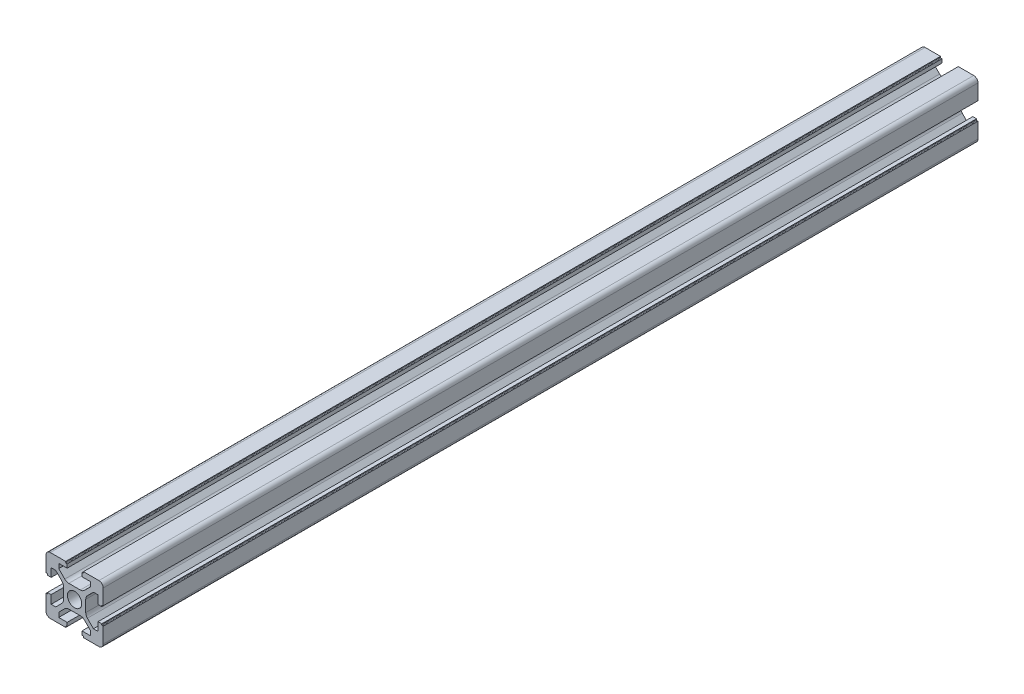
SolidWorks part; units mm, degrees
ref_plane "Спереди" through (0, 0, 0) normal (0, 0, 1) x (1, 0, 0)
ref_plane "Сверху" through (0, 0, 0) normal (0, 1, 0) x (1, 0, 0)
ref_plane "Справа" through (0, 0, 0) normal (1, 0, 0) x (0, 0, -1)
sketch "Sketch1" plane through (0, 0, 0) normal (0, 0, 1) x (1, 0, 0)
  line L0 (0, 10) -> (0, -10) construction
  line L1 (-10, -10) -> (10, -10) construction
  line L2 (-10, -10) -> (-10, 10) construction
  line L3 (-10, 10) -> (10, 10) construction
  line L4 (10, -10) -> (10, 10) construction
  line L5 (-10, -10) -> (10, 10) construction
  line L6 (-10, 10) -> (10, -10) construction
  line L7 (-10, 0) -> (10, 0) construction
  line L8 (0, 3.9) -> (-2.0109, 3.9)
  line L9 (-3.4251, 4.4858) -> (-5.5393, 6.6)
  line L10 (-5.5393, 6.6) -> (-5.5393, 8.2)
  line L11 (-5.5393, 8.2) -> (-2.6, 8.2)
  line L12 (-2.6, 8.2) -> (-2.6, 9.5)
  line L13 (-2.6, 9.5) -> (-2.9, 9.5)
  line L14 (-3.1, 9.7) -> (-3.1, 10)
  line L15 (-3.1, 10) -> (-8.5, 10)
  line L16 (-10, 3.1) -> (-10, 8.5)
  line L17 (-9.7, 3.1) -> (-10, 3.1)
  line L18 (-9.5, 2.6) -> (-9.5, 2.9)
  line L19 (-8.2, 2.6) -> (-9.5, 2.6)
  line L20 (-8.2, 5.5393) -> (-8.2, 2.6)
  line L21 (-6.6, 5.5393) -> (-8.2, 5.5393)
  line L22 (-4.4858, 3.4251) -> (-6.6, 5.5393)
  line L23 (-3.9, 0) -> (-3.9, 2.0109)
  line L24 (3.9, 0) -> (3.9, 2.0109)
  line L25 (4.4858, 3.4251) -> (6.6, 5.5393)
  line L26 (6.6, 5.5393) -> (8.2, 5.5393)
  line L27 (8.2, 5.5393) -> (8.2, 2.6)
  line L28 (8.2, 2.6) -> (9.5, 2.6)
  line L29 (9.5, 2.6) -> (9.5, 2.9)
  line L30 (9.7, 3.1) -> (10, 3.1)
  line L31 (10, 3.1) -> (10, 8.5)
  line L32 (3.1, 10) -> (8.5, 10)
  line L33 (3.1, 9.7) -> (3.1, 10)
  line L34 (2.6, 9.5) -> (2.9, 9.5)
  line L35 (2.6, 8.2) -> (2.6, 9.5)
  line L36 (5.5393, 8.2) -> (2.6, 8.2)
  line L37 (5.5393, 6.6) -> (5.5393, 8.2)
  line L38 (3.4251, 4.4858) -> (5.5393, 6.6)
  line L39 (0, 3.9) -> (2.0109, 3.9)
  line L40 (0, -3.9) -> (2.0109, -3.9)
  line L41 (3.4251, -4.4858) -> (5.5393, -6.6)
  line L42 (5.5393, -6.6) -> (5.5393, -8.2)
  line L43 (5.5393, -8.2) -> (2.6, -8.2)
  line L44 (2.6, -8.2) -> (2.6, -9.5)
  line L45 (2.6, -9.5) -> (2.9, -9.5)
  line L46 (3.1, -9.7) -> (3.1, -10)
  line L47 (3.1, -10) -> (8.5, -10)
  line L48 (10, -3.1) -> (10, -8.5)
  line L49 (9.7, -3.1) -> (10, -3.1)
  line L50 (9.5, -2.6) -> (9.5, -2.9)
  line L51 (8.2, -2.6) -> (9.5, -2.6)
  line L52 (8.2, -5.5393) -> (8.2, -2.6)
  line L53 (6.6, -5.5393) -> (8.2, -5.5393)
  line L54 (4.4858, -3.4251) -> (6.6, -5.5393)
  line L55 (3.9, 0) -> (3.9, -2.0109)
  line L56 (-3.9, 0) -> (-3.9, -2.0109)
  line L57 (-4.4858, -3.4251) -> (-6.6, -5.5393)
  line L58 (-6.6, -5.5393) -> (-8.2, -5.5393)
  line L59 (-8.2, -5.5393) -> (-8.2, -2.6)
  line L60 (-8.2, -2.6) -> (-9.5, -2.6)
  line L61 (-9.5, -2.6) -> (-9.5, -2.9)
  line L62 (-9.7, -3.1) -> (-10, -3.1)
  line L63 (-10, -3.1) -> (-10, -8.5)
  line L64 (-3.1, -10) -> (-8.5, -10)
  line L65 (-3.1, -9.7) -> (-3.1, -10)
  line L66 (-2.6, -9.5) -> (-2.9, -9.5)
  line L67 (-2.6, -8.2) -> (-2.6, -9.5)
  line L68 (-5.5393, -8.2) -> (-2.6, -8.2)
  line L69 (-5.5393, -6.6) -> (-5.5393, -8.2)
  line L70 (-3.4251, -4.4858) -> (-5.5393, -6.6)
  line L71 (0, -3.9) -> (-2.0109, -3.9)
  circle A0 centre (0, 0) radius 2.5
  arc A1 (-8.5, 10) -> (-10, 8.5) centre (-8.5, 8.5) ccw
  arc A2 (-2.0109, 3.9) -> (-3.4251, 4.4858) centre (-2.0109, 5.9) cw
  arc A3 (-2.9, 9.5) -> (-3.1, 9.7) centre (-2.9, 9.7) cw
  arc A4 (-9.5, 2.9) -> (-9.7, 3.1) centre (-9.7, 2.9) ccw
  arc A5 (-3.9, 2.0109) -> (-4.4858, 3.4251) centre (-5.9, 2.0109) ccw
  arc A6 (10, 8.5) -> (8.5, 10) centre (8.5, 8.5) ccw
  arc A7 (3.9, 2.0109) -> (4.4858, 3.4251) centre (5.9, 2.0109) cw
  arc A8 (9.5, 2.9) -> (9.7, 3.1) centre (9.7, 2.9) cw
  arc A9 (2.9, 9.5) -> (3.1, 9.7) centre (2.9, 9.7) ccw
  arc A10 (2.0109, 3.9) -> (3.4251, 4.4858) centre (2.0109, 5.9) ccw
  arc A11 (8.5, -10) -> (10, -8.5) centre (8.5, -8.5) ccw
  arc A12 (2.0109, -3.9) -> (3.4251, -4.4858) centre (2.0109, -5.9) cw
  arc A13 (2.9, -9.5) -> (3.1, -9.7) centre (2.9, -9.7) cw
  arc A14 (9.5, -2.9) -> (9.7, -3.1) centre (9.7, -2.9) ccw
  arc A15 (3.9, -2.0109) -> (4.4858, -3.4251) centre (5.9, -2.0109) ccw
  arc A16 (-10, -8.5) -> (-8.5, -10) centre (-8.5, -8.5) ccw
  arc A17 (-3.9, -2.0109) -> (-4.4858, -3.4251) centre (-5.9, -2.0109) cw
  arc A18 (-9.5, -2.9) -> (-9.7, -3.1) centre (-9.7, -2.9) cw
  arc A19 (-2.9, -9.5) -> (-3.1, -9.7) centre (-2.9, -9.7) ccw
  arc A20 (-2.0109, -3.9) -> (-3.4251, -4.4858) centre (-2.0109, -5.9) ccw
  point P0 (0, 0)
  point P42 (0, 0)
  point P70 (0, 0)
  point P98 (0, 0)
  point P126 (0, 0)
  dimension "D3" = 5
  dimension "D4" = 3
  dimension "D12" = 2
  dimension "D13" = 0.2
  dimension "D1" = 20
  dimension "D2" = 20
  dimension "D5" = 5.2
  dimension "D6" = 6.2
  dimension "D7" = 1.8
  dimension "D8" = 0.5
  dimension "D9" = 3.4
  dimension "D10" = 1.5
  dimension "D11" = 6.1
  dimension "D14" = 4
extrude "Extrude1" add sketch "Sketch1" along normal blind 306
